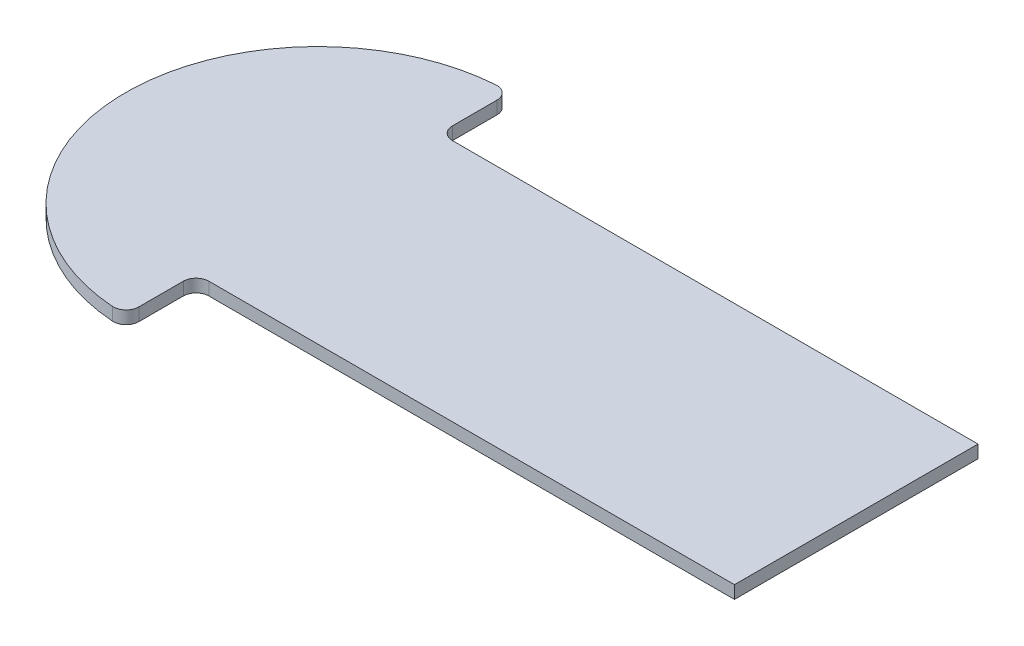
SolidWorks part; units mm, degrees
ref_plane "Front Plane" through (0, 0, 0) normal (0, 0, 1) x (1, 0, 0)
ref_plane "Top Plane" through (0, 0, 0) normal (0, 1, 0) x (1, 0, 0)
ref_plane "Right Plane" through (0, 0, 0) normal (1, 0, 0) x (0, 0, -1)
sketch "Sketch1" plane through (0, 0, 0) normal (0, 1, 0) x (1, 0, 0)
  line L0 (-21, 15) -> (-21, 9.5)
  line L1 (21, -9.5) -> (-21, -9.5)
  line L2 (21, -9.5) -> (21, 9.5)
  line L3 (21, 9.5) -> (-21, 9.5)
  line L4 (-21, -9.5) -> (-21, 9.5)
  line L5 (21, -9.5) -> (-21, 9.5) construction
  line L6 (21, 9.5) -> (-21, -9.5) construction
  line L7 (-21, -15) -> (-21, -9.5)
  arc A0 (-21, 15) -> (-21, -15) centre (-21, 0) ccw
  point P0 (0, 0)
  dimension "D3" = 15
  dimension "D1" = 19
  dimension "D2" = 42
extrude "Boss-Extrude1" add sketch "Sketch1" along normal blind 1 contours L0 A0 L7 L4 | L4 L1 L2 L3
fillet "Fillet1" radius 1 4 edges at (-21, 0.5, 9.5) (-21, 0.5, -9.5) (-21, 0.5, -15) (-21, 0.5, 15)
